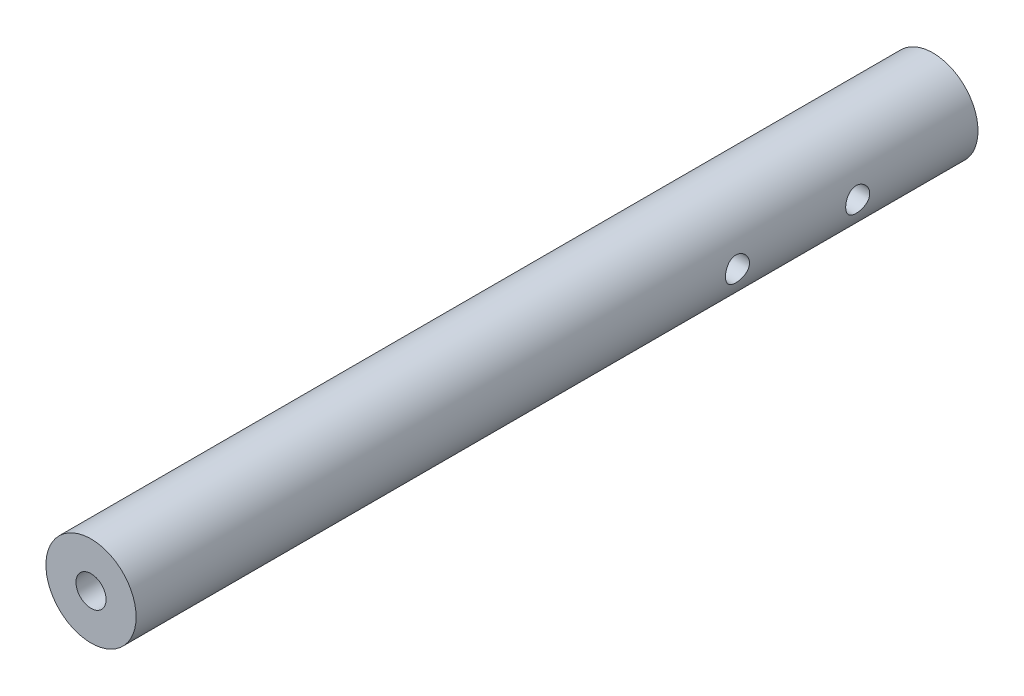
SolidWorks part; units mm, degrees
ref_plane "Front Plane" through (0, 0, 0) normal (0, 0, 1) x (1, 0, 0)
ref_plane "Top Plane" through (0, 0, 0) normal (0, 1, 0) x (1, 0, 0)
ref_plane "Right Plane" through (0, 0, 0) normal (1, 0, 0) x (0, 0, -1)
sketch "Sketch1" plane through (0, 0, 0) normal (0, 0, 1) x (1, 0, 0)
  circle A0 centre (0, 0) radius 7.5
  circle A1 centre (0, 0) radius 2.5
  dimension "D1" = 15
  dimension "D2" = 5
extrude "Boss-Extrude1" add sketch "Sketch1" along normal blind 140
ref_plane "Plane1" through (-7.5, 0, 0) normal (-1, 0, 0) x (0, 0, 1)
sketch "Sketch2" plane through (-7.5, 0, 0) normal (-1, 0, 0) x (0, 0, 1)
  line L0 (0, 0) -> (140, 0) construction
  line L1 (140, -7.5) -> (140, 7.5) construction
  circle A0 centre (20, 0) radius 2
  circle A1 centre (40, 0) radius 2
  dimension "D1" = 4
  dimension "D2" = 4
  dimension "D3" = 20
  dimension "D4" = 20
extrude "Cut-Extrude1" cut sketch "Sketch2" against normal blind 16
